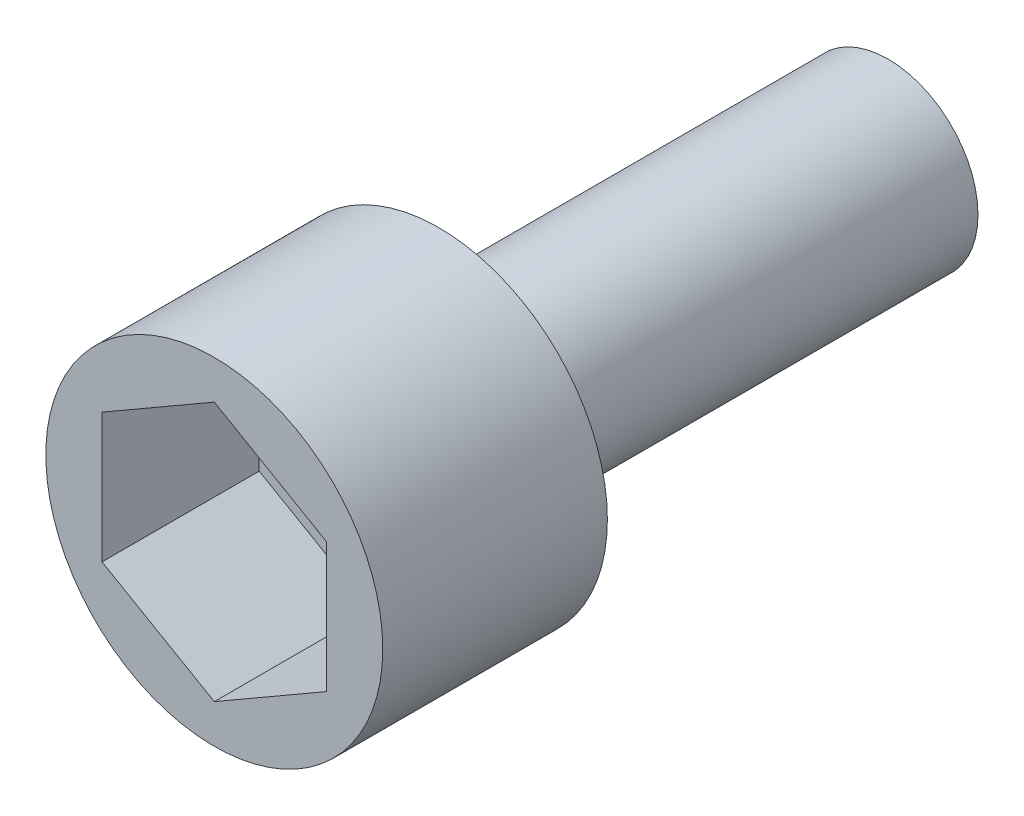
SolidWorks part; units mm, degrees
ref_plane "Front Plane" through (0, 0, 0) normal (0, 0, 1) x (1, 0, 0)
ref_plane "Top Plane" through (0, 0, 0) normal (0, 1, 0) x (1, 0, 0)
ref_plane "Right Plane" through (0, 0, 0) normal (1, 0, 0) x (0, 0, -1)
sketch "Sketch1" plane through (0, 0, 0) normal (0, 0, 1) x (1, 0, 0)
  circle A0 centre (0, 0) radius 7.5
  dimension "D1" = 15
extrude "Boss-Extrude1" add sketch "Sketch1" along normal blind 10
sketch "Sketch2" plane through (0, 0, 10) normal (0, 0, 1) x (1, 0, 0)
  line L1 (5, 2.8868) -> (0, 5.7735)
  line L2 (0, 5.7735) -> (-5, 2.8868)
  line L3 (-5, 2.8868) -> (-5, -2.8868)
  line L4 (-5, -2.8868) -> (0, -5.7735)
  line L5 (0, -5.7735) -> (5, -2.8868)
  line L6 (5, -2.8868) -> (5, 2.8868)
  circle A0 centre (0, 0) radius 5 construction
  dimension "D1" = 10
sketch "Sketch3" plane through (0, 0, 0) normal (0, 0, -1) x (-1, 0, 0)
  circle A0 centre (0, 0) radius 4
  dimension "D1" = 8
extrude "Boss-Extrude2" add sketch "Sketch3" along normal blind 20
extrude "Cut-Extrude1" cut sketch "Sketch2" against normal blind 7
